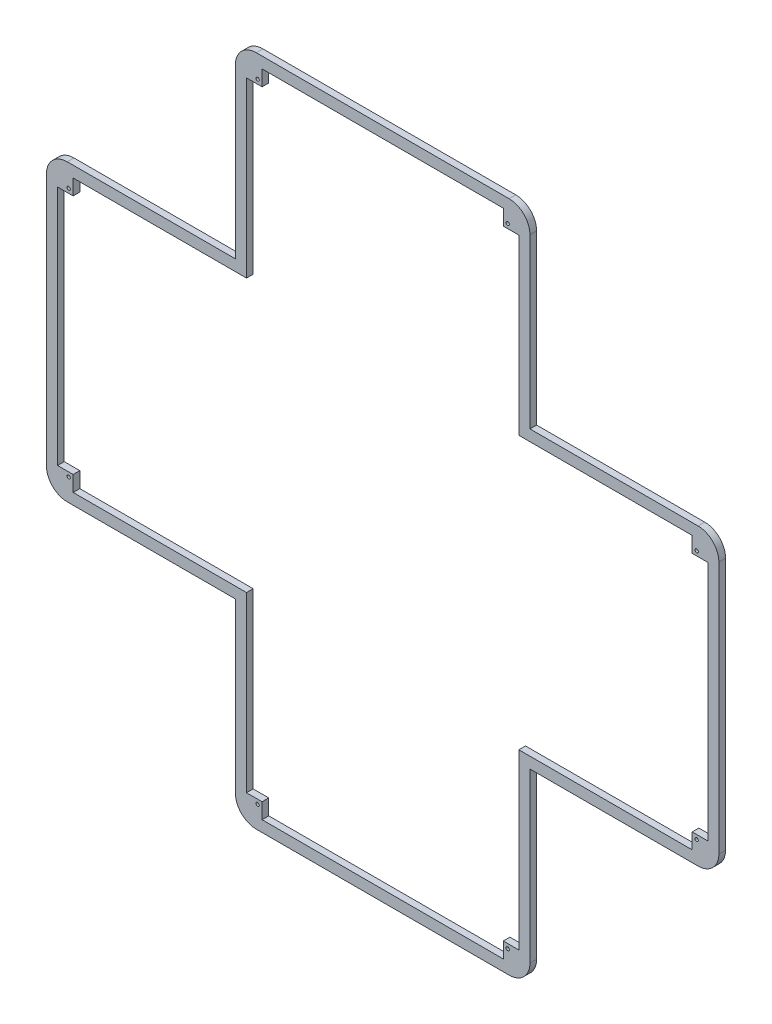
SolidWorks part; units mm, degrees
material "Maple"
ref_plane "Alzado" through (0, 0, 0) normal (0, 0, 1) x (1, 0, 0)
ref_plane "Planta" through (0, 0, 0) normal (0, 1, 0) x (1, 0, 0)
ref_plane "Vista lateral" through (0, 0, 0) normal (1, 0, 0) x (0, 0, -1)
sketch "Croquis1" plane through (0, 0, 0) normal (0, 0, 1) x (1, 0, 0)
  line L0 (-278.5, 122.5) -> (-122.5, 122.5)
  line L1 (-283.764, 132.5) -> (-132.5, 132.5)
  line L2 (-132.5, 132.5) -> (-132.5, 283.764)
  line L3 (-122.5, 122.5) -> (-122.5, 278.5)
  line L4 (132.5, 283.764) -> (132.5, 132.5)
  line L5 (132.5, 132.5) -> (283.764, 132.5)
  line L6 (-108.5, 292.5) -> (108.5, 292.5)
  line L7 (283.764, -132.5) -> (132.5, -132.5)
  line L8 (132.5, -132.5) -> (132.5, -283.764)
  line L9 (-113.764, -302.5) -> (113.764, -302.5)
  line L10 (-132.5, -283.764) -> (-132.5, -132.5)
  line L11 (-283.764, -132.5) -> (-132.5, -132.5)
  line L12 (302.5, 113.764) -> (302.5, -113.764)
  line L13 (-302.5, 113.764) -> (-302.5, -113.764)
  line L14 (-113.764, 302.5) -> (113.764, 302.5)
  line L15 (122.5, 278.5) -> (122.5, 122.5)
  line L16 (122.5, 122.5) -> (278.5, 122.5)
  line L17 (292.5, 108.5) -> (292.5, -108.5)
  line L18 (278.5, -122.5) -> (122.5, -122.5)
  line L19 (122.5, -122.5) -> (122.5, -278.5)
  line L20 (-108.5, -292.5) -> (108.5, -292.5)
  line L21 (-122.5, -278.5) -> (-122.5, -122.5)
  line L22 (-278.5, -122.5) -> (-122.5, -122.5)
  line L23 (-292.5, 108.5) -> (-292.5, -108.5)
  line L24 (-278.5, 122.5) -> (-278.5, 108.5)
  line L25 (-278.5, 108.5) -> (-292.5, 108.5)
  line L26 (-283.764, 122.5) -> (-122.5, 122.5) construction
  line L27 (-292.5, 113.764) -> (-292.5, -113.764) construction
  line L28 (-292.5, -108.5) -> (-278.5, -108.5)
  line L29 (-278.5, -108.5) -> (-278.5, -122.5)
  line L30 (-283.764, -122.5) -> (-122.5, -122.5) construction
  line L31 (-108.5, 292.5) -> (-108.5, 278.5)
  line L32 (-108.5, 278.5) -> (-122.5, 278.5)
  line L33 (-113.764, 292.5) -> (113.764, 292.5) construction
  line L34 (-122.5, 122.5) -> (-122.5, 283.764) construction
  line L35 (108.5, 292.5) -> (108.5, 278.5)
  line L36 (108.5, 278.5) -> (122.5, 278.5)
  line L37 (122.5, 283.764) -> (122.5, 122.5) construction
  line L38 (278.5, 122.5) -> (278.5, 108.5)
  line L39 (278.5, 108.5) -> (292.5, 108.5)
  line L40 (122.5, 122.5) -> (283.764, 122.5) construction
  line L41 (292.5, 113.764) -> (292.5, -113.764) construction
  line L42 (292.5, -108.5) -> (278.5, -108.5)
  line L43 (278.5, -108.5) -> (278.5, -122.5)
  line L44 (283.764, -122.5) -> (122.5, -122.5) construction
  line L45 (122.5, -278.5) -> (108.5, -278.5)
  line L46 (108.5, -278.5) -> (108.5, -292.5)
  line L47 (122.5, -122.5) -> (122.5, -283.764) construction
  line L48 (-113.764, -292.5) -> (113.764, -292.5) construction
  line L49 (-122.5, -278.5) -> (-108.5, -278.5)
  line L50 (-108.5, -278.5) -> (-108.5, -292.5)
  line L51 (-122.5, -283.764) -> (-122.5, -122.5) construction
  arc A0 (-302.5, 113.764) -> (-283.764, 132.5) centre (-283.764, 113.764) cw
  arc A1 (-132.5, 283.764) -> (-113.764, 302.5) centre (-113.764, 283.764) cw
  arc A2 (113.764, 302.5) -> (132.5, 283.764) centre (113.764, 283.764) cw
  arc A3 (283.764, 132.5) -> (302.5, 113.764) centre (283.764, 113.764) cw
  arc A4 (302.5, -113.764) -> (283.764, -132.5) centre (283.764, -113.764) cw
  arc A5 (132.5, -283.764) -> (113.764, -302.5) centre (113.764, -283.764) cw
  arc A6 (-113.764, -302.5) -> (-132.5, -283.764) centre (-113.764, -283.764) cw
  arc A7 (-283.764, -132.5) -> (-302.5, -113.764) centre (-283.764, -113.764) cw
  circle A8 centre (-282.5, 112.5) radius 1.5
  circle A9 centre (-282.5, -112.5) radius 1.5
  circle A10 centre (-112.5, -282.5) radius 1.5
  circle A11 centre (112.5, -282.5) radius 1.5
  circle A12 centre (282.5, -112.5) radius 1.5
  circle A13 centre (282.5, 112.5) radius 1.5
  circle A14 centre (-112.5, 282.5) radius 1.5
  circle A15 centre (112.5, 282.5) radius 1.5
  arc A16 (-292.5, 113.764) -> (-283.764, 122.5) centre (-283.764, 113.764) cw construction
  arc A17 (-283.764, -122.5) -> (-292.5, -113.764) centre (-283.764, -113.764) cw construction
  arc A18 (-122.5, 283.764) -> (-113.764, 292.5) centre (-113.764, 283.764) cw construction
  arc A19 (113.764, 292.5) -> (122.5, 283.764) centre (113.764, 283.764) cw construction
  arc A20 (283.764, 122.5) -> (292.5, 113.764) centre (283.764, 113.764) cw construction
  arc A21 (292.5, -113.764) -> (283.764, -122.5) centre (283.764, -113.764) cw construction
  arc A22 (122.5, -283.764) -> (113.764, -292.5) centre (113.764, -283.764) cw construction
  arc A23 (-113.764, -292.5) -> (-122.5, -283.764) centre (-113.764, -283.764) cw construction
  point P2 (-302.5, 132.5)
  point P8 (-132.5, 302.5)
  point P14 (132.5, 302.5)
  point P18 (302.5, 132.5)
  point P33 (-302.5, -132.5)
  dimension "D5" = 265
  dimension "D7" = 18.736
  dimension "D8" = 18.736
  dimension "D28" = 3
  dimension "D30" = 20
  dimension "D31" = 20
  dimension "D32" = 20
  dimension "D33" = 3
  dimension "D34" = 3
  dimension "D35" = 3
  dimension "D36" = 20
  dimension "D37" = 20
  dimension "D38" = 20
  dimension "D39" = 20
  dimension "D40" = 20
  dimension "D41" = 20
  dimension "D42" = 3
  dimension "D43" = 3
  dimension "D44" = 3
  dimension "D45" = 20
  dimension "D46" = 20
  dimension "D47" = 20
  dimension "D49" = 3
  dimension "D50" = 20
  dimension "D1" = 170
  dimension "D2" = 170
  dimension "D3" = 170
  dimension "D4" = 170
  dimension "D6" = 265
  dimension "D9" = 302.5
  dimension "D10" = 302.5
  dimension "D11" = 10
  dimension "D12" = 24
  dimension "D13" = 24
  dimension "D14" = 24
  dimension "D15" = 24
  dimension "D16" = 24
  dimension "D17" = 24
  dimension "D18" = 24
  dimension "D19" = 24
  dimension "D20" = 24
  dimension "D21" = 24
  dimension "D22" = 24
  dimension "D23" = 24
  dimension "D24" = 24
  dimension "D25" = 24
  dimension "D26" = 24
  dimension "D27" = 24
  dimension "D29" = 20
  dimension "D48" = 20
  dimension "D51" = 20
extrude "Saliente-Extruir1" add sketch "Croquis1" along normal blind 6
sketch "Croquis2" plane through (0, 0, 6) normal (0, 0, 1) x (1, 0, 0)
  line L0 (-122.5, 122.5) -> (-132.5, 132.5) construction
  line L1 (0, 292.5) -> (0, 302.5) construction
  line L2 (108.5, 292.5) -> (-108.5, 292.5) construction
  line L3 (113.764, 302.5) -> (-113.764, 302.5) construction
  line L4 (0, 302.5) -> (-113.764, 302.5)
  line L5 (-132.5, 283.764) -> (-132.5, 132.5)
  line L6 (-132.5, 132.5) -> (-122.5, 122.5)
  line L7 (-122.5, 122.5) -> (-122.5, 278.5)
  line L8 (-108.5, 292.5) -> (0, 292.5)
  line L9 (0, 292.5) -> (0, 302.5)
  line L10 (-108.5, 292.5) -> (-108.5, 278.5)
  line L11 (-108.5, 278.5) -> (-122.5, 278.5)
  arc A0 (-113.764, 302.5) -> (-132.5, 283.764) centre (-113.764, 283.764) ccw
